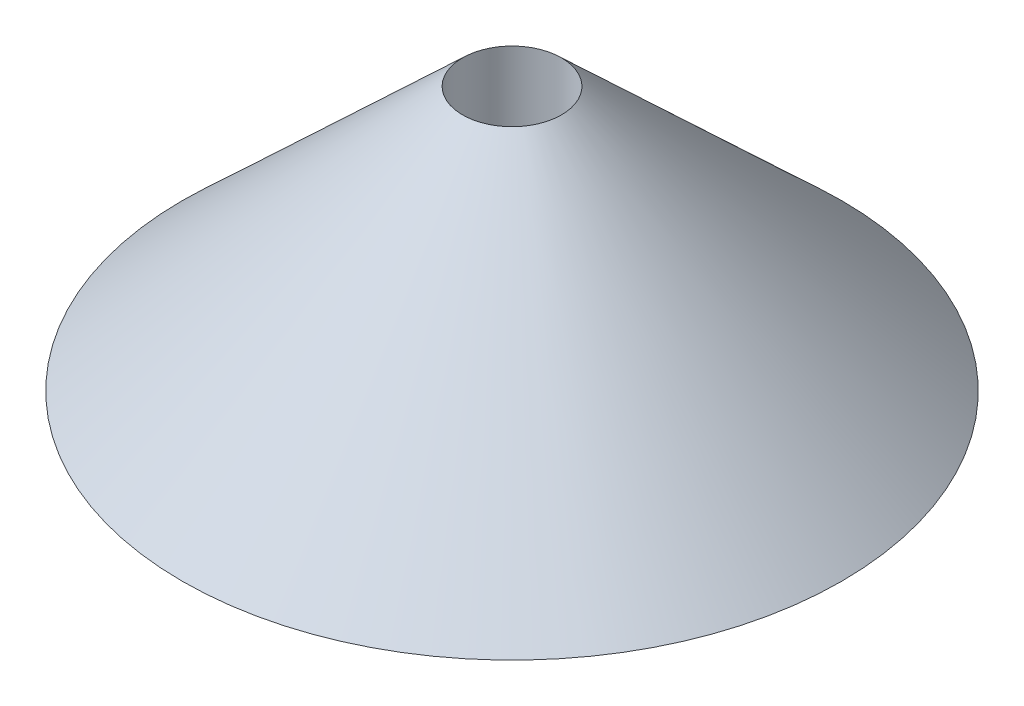
SolidWorks part; units mm, degrees
ref_plane "Alzado" through (0, 0, 0) normal (0, 0, 1) x (1, 0, 0)
ref_plane "Planta" through (0, 0, 0) normal (0, 1, 0) x (1, 0, 0)
ref_plane "Vista lateral" through (0, 0, 0) normal (1, 0, 0) x (0, 0, -1)
sketch "Croquis2" plane through (0, 0, 0) normal (0, 0, 1) x (1, 0, 0)
  line L0 (-32.8121, 3.6393) -> (-42.8121, 3.6393)
  line L1 (-32.8121, 3.6393) -> (-32.8121, 6.6393)
  line L2 (-32.8121, 6.6393) -> (-34.3121, 6.6393)
  line L3 (-34.3121, 6.6393) -> (-34.3121, 11.6393)
  line L4 (-34.3121, 11.6393) -> (-42.8121, 3.6393)
revolve "Revolución1" add sketch "Croquis2" angle 360 about L1
